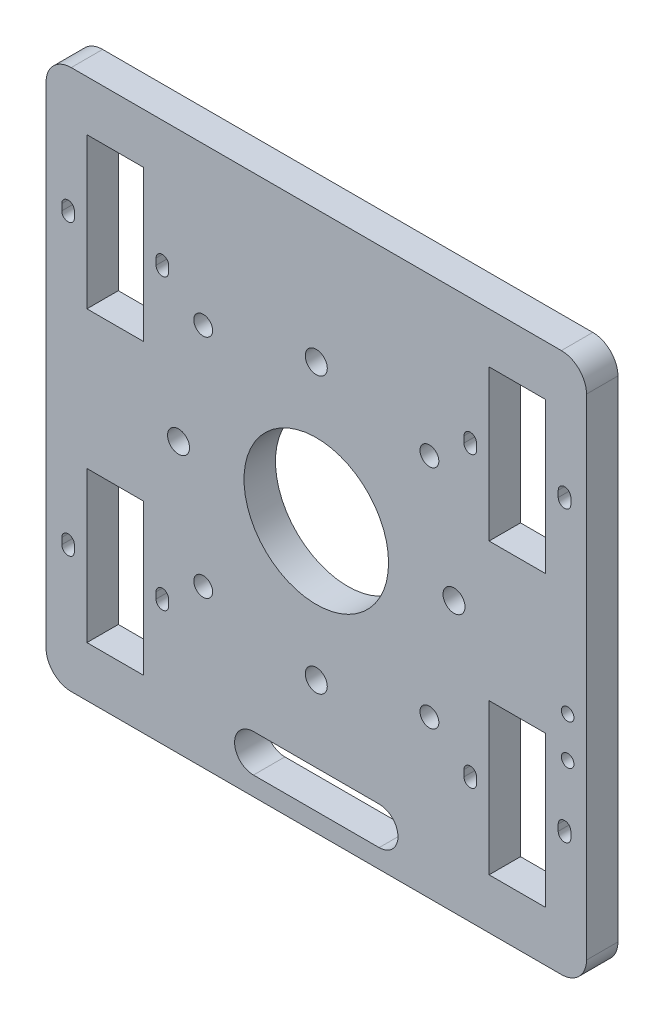
SolidWorks part; units mm, degrees
material "Maple"
ref_plane "Front Plane" through (0, 0, 0) normal (0, 0, 1) x (1, 0, 0)
ref_plane "Top Plane" through (0, 0, 0) normal (0, 1, 0) x (1, 0, 0)
ref_plane "Right Plane" through (0, 0, 0) normal (1, 0, 0) x (0, 0, -1)
sketch "Sketch1" plane through (0, 0, 0) normal (0, 0, 1) x (1, 0, 0)
  line L0 (67.5, 66.5) -> (67.5, 65.5) construction
  line L1 (0, 86) -> (86, 86)
  line L2 (0, 86) -> (0, 0)
  line L3 (0, 0) -> (86, 0)
  line L4 (86, 86) -> (86, 0)
  line L5 (70.5, 78) -> (79.5, 78)
  line L6 (70.5, 78) -> (70.5, 54)
  line L7 (70.5, 54) -> (79.5, 54) construction
  line L8 (79.5, 78) -> (79.5, 54)
  line L9 (68.5, 66.5) -> (68.5, 65.5)
  line L10 (66.5, 66.5) -> (66.5, 65.5)
  line L11 (75, 78) -> (75, 54) construction
  line L12 (67.5, 66) -> (75, 66) construction
  line L13 (82.5, 66.5) -> (82.5, 65.5) construction
  line L14 (81.5, 66.5) -> (81.5, 65.5)
  line L15 (83.5, 66.5) -> (83.5, 65.5)
  line L16 (70.5, 54) -> (79.5, 54)
  line L17 (67.5, 19.5) -> (67.5, 20.5) construction
  line L18 (68.5, 19.5) -> (68.5, 20.5)
  line L19 (66.5, 19.5) -> (66.5, 20.5)
  line L20 (82.5, 19.5) -> (82.5, 20.5) construction
  line L21 (81.5, 19.5) -> (81.5, 20.5)
  line L22 (83.5, 19.5) -> (83.5, 20.5)
  line L23 (67.5, 20) -> (75, 20) construction
  line L24 (75, 8) -> (75, 32) construction
  line L25 (70.5, 32) -> (79.5, 32) construction
  line L26 (70.5, 32) -> (79.5, 32)
  line L27 (79.5, 8) -> (79.5, 32)
  line L28 (70.5, 8) -> (70.5, 32)
  line L29 (70.5, 8) -> (79.5, 8)
  line L30 (18.5, 66.5) -> (18.5, 65.5) construction
  line L31 (17.5, 66.5) -> (17.5, 65.5)
  line L32 (19.5, 66.5) -> (19.5, 65.5)
  line L33 (3.5, 66.5) -> (3.5, 65.5) construction
  line L34 (4.5, 66.5) -> (4.5, 65.5)
  line L35 (2.5, 66.5) -> (2.5, 65.5)
  line L36 (18.5, 19.5) -> (18.5, 20.5) construction
  line L37 (17.5, 19.5) -> (17.5, 20.5)
  line L38 (19.5, 19.5) -> (19.5, 20.5)
  line L39 (3.5, 19.5) -> (3.5, 20.5) construction
  line L40 (4.5, 19.5) -> (4.5, 20.5)
  line L41 (2.5, 19.5) -> (2.5, 20.5)
  line L42 (15.5, 32) -> (6.5, 32) construction
  line L43 (11, 8) -> (11, 32) construction
  line L44 (18.5, 20) -> (11, 20) construction
  line L45 (18.5, 66) -> (11, 66) construction
  line L46 (11, 78) -> (11, 54) construction
  line L47 (15.5, 54) -> (6.5, 54) construction
  line L48 (15.5, 8) -> (6.5, 8)
  line L49 (15.5, 8) -> (15.5, 32)
  line L50 (6.5, 8) -> (6.5, 32)
  line L51 (15.5, 32) -> (6.5, 32)
  line L52 (15.5, 54) -> (6.5, 54)
  line L53 (6.5, 78) -> (6.5, 54)
  line L54 (15.5, 78) -> (15.5, 54)
  line L55 (15.5, 78) -> (6.5, 78)
  line L56 (43, 21.0797) -> (43, 0) construction
  line L57 (21.0797, 43) -> (0, 43) construction
  line L58 (25, 25) -> (61, 61) construction
  line L59 (25, 61) -> (61, 61) construction
  line L60 (25, 61) -> (25, 25) construction
  line L61 (25, 25) -> (61, 25) construction
  line L62 (61, 61) -> (61, 25) construction
  line L92 (43, 64.9203) -> (43, 21.0797) construction
  line L93 (43, 64.9203) -> (64.9203, 43) construction
  line L94 (43, 64.9203) -> (21.0797, 43) construction
  line L95 (21.0797, 43) -> (43, 21.0797) construction
  line L96 (64.9203, 43) -> (43, 21.0797) construction
  line L99 (43, 43) -> (54, 43) construction
  arc A0 (68.5, 66.5) -> (66.5, 66.5) centre (67.5, 66.5) ccw
  arc A1 (66.5, 65.5) -> (68.5, 65.5) centre (67.5, 65.5) ccw
  arc A2 (81.5, 66.5) -> (83.5, 66.5) centre (82.5, 66.5) cw
  arc A3 (83.5, 65.5) -> (81.5, 65.5) centre (82.5, 65.5) cw
  arc A4 (68.5, 19.5) -> (66.5, 19.5) centre (67.5, 19.5) cw
  arc A5 (66.5, 20.5) -> (68.5, 20.5) centre (67.5, 20.5) cw
  arc A6 (81.5, 19.5) -> (83.5, 19.5) centre (82.5, 19.5) ccw
  arc A7 (83.5, 20.5) -> (81.5, 20.5) centre (82.5, 20.5) ccw
  arc A8 (17.5, 66.5) -> (19.5, 66.5) centre (18.5, 66.5) cw
  arc A9 (19.5, 65.5) -> (17.5, 65.5) centre (18.5, 65.5) cw
  arc A10 (4.5, 66.5) -> (2.5, 66.5) centre (3.5, 66.5) ccw
  arc A11 (2.5, 65.5) -> (4.5, 65.5) centre (3.5, 65.5) ccw
  arc A12 (17.5, 19.5) -> (19.5, 19.5) centre (18.5, 19.5) ccw
  arc A13 (19.5, 20.5) -> (17.5, 20.5) centre (18.5, 20.5) ccw
  arc A14 (4.5, 19.5) -> (2.5, 19.5) centre (3.5, 19.5) cw
  arc A15 (2.5, 20.5) -> (4.5, 20.5) centre (3.5, 20.5) cw
  circle A16 centre (25, 61) radius 1.5
  circle A17 centre (61, 61) radius 1.5
  circle A18 centre (25, 25) radius 1.5
  circle A19 centre (61, 25) radius 1.5
  circle A32 centre (43, 43) radius 11.5
  circle A33 centre (43, 64.9203) radius 1.75
  circle A34 centre (64.9203, 43) radius 1.75
  circle A35 centre (43, 21.0797) radius 1.75
  circle A36 centre (21.0797, 43) radius 1.75
  point P10 (67.5, 66)
  point P20 (82.5, 66)
  point P29 (67.5, 20)
  point P37 (82.5, 20)
  point P52 (18.5, 66)
  point P59 (3.5, 66)
  point P66 (18.5, 20)
  point P73 (3.5, 20)
  point P96 (43, 43)
  dimension "D17" = 3.5
  dimension "D18" = 23
  dimension "D9" = 3
  dimension "D2" = 1
  dimension "D3" = 9
  dimension "D4" = 24
  dimension "D5" = 2
  dimension "D6" = 7.5
  dimension "D7" = 8
  dimension "D8" = 36
  dimension "D11" = 32
  dimension "D14" = 11
  dimension "D19" = 31
extrude "Boss-Extrude1" add sketch "Sketch1" along normal blind 5
fillet "Fillet1" radius 4 4 edges at (86, 0, 2.5) (0, 0, 2.5) (0, 86, 2.5) (86, 86, 2.5)
sketch "Sketch2" plane through (0, 0, 5) normal (0, 0, 1) x (1, 0, 0)
  line L0 (33, 6) -> (53, 6) construction
  line L1 (33, 9) -> (53, 9)
  line L2 (86, 4) -> (86, 82) construction
  line L3 (4, 0) -> (82, 0) construction
  line L4 (33, 3) -> (53, 3)
  line L5 (43, 43) -> (43, 6) construction
  circle A0 centre (83, 36.4) radius 1
  circle A1 centre (83, 30) radius 1
  arc A2 (33, 9) -> (33, 3) centre (33, 6) ccw
  arc A3 (53, 3) -> (53, 9) centre (53, 6) ccw
  point P10 (43, 6)
  dimension "D1" = 3
  dimension "D4" = 2
  dimension "D2" = 6.4
  dimension "D3" = 30
  dimension "D5" = 6
  dimension "D6" = 6
  dimension "D7" = 20
extrude "Cut-Extrude1" cut sketch "Sketch2" against normal through all
